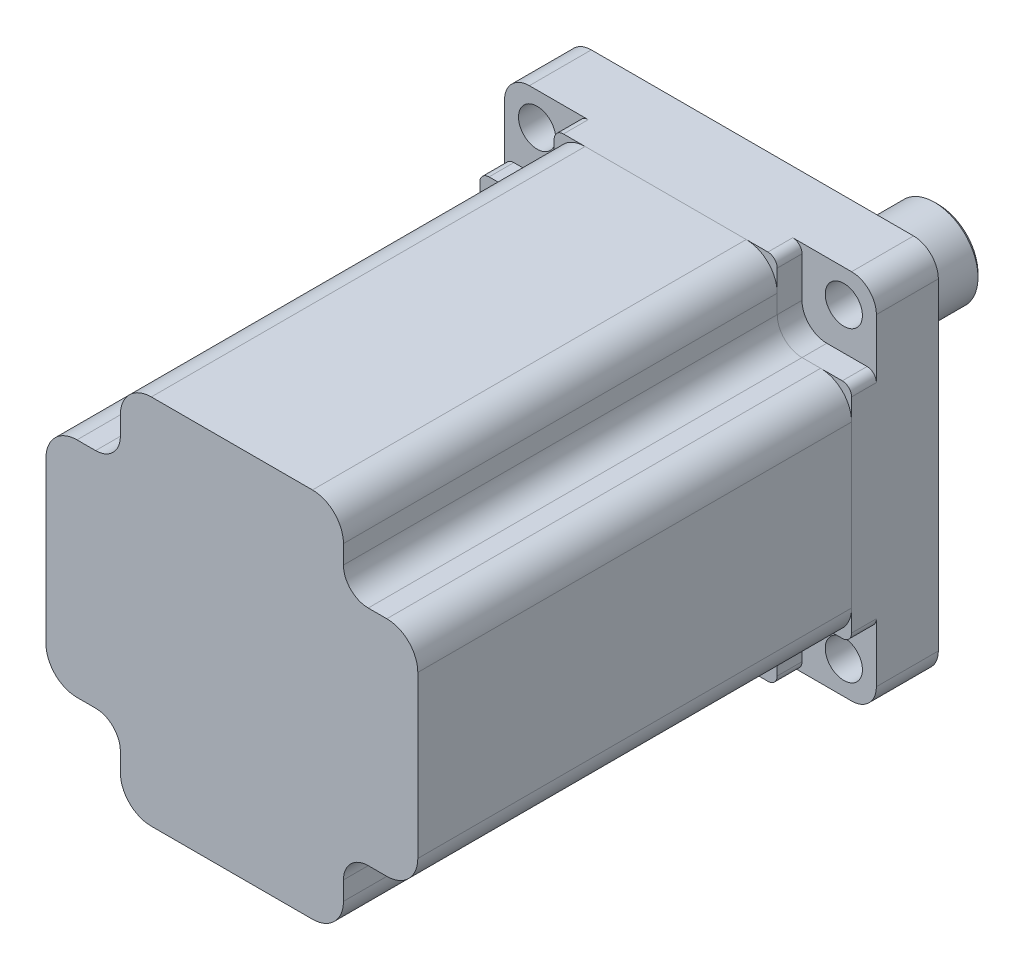
SolidWorks part; units mm, degrees
ref_plane "前视基准面" through (0, 0, 0) normal (0, 0, 1) x (1, 0, 0)
ref_plane "上视基准面" through (0, 0, 0) normal (0, 1, 0) x (1, 0, 0)
ref_plane "右视基准面" through (0, 0, 0) normal (1, 0, 0) x (0, 0, -1)
ref_plane "基准面4" through (0, 0, 0) normal (0, 0, -1) x (-1, 0, 0)
sketch "草图1" plane through (0, 0, 0) normal (0, 0, -1) x (-1, 0, 0)
  line L0 (-30, 30) -> (-30, -30)
  line L1 (-30, -30) -> (30, -30)
  line L2 (30, -30) -> (30, 30)
  line L3 (30, 30) -> (-30, 30)
extrude "凸台-拉伸1" add sketch "草图1" against normal blind 14
sketch "草图2" plane through (30, 0, 0) normal (1, 0, 0) x (0, 0, -1)
  line L0 (-10, 18) -> (-10, 30)
  line L1 (-10, 30) -> (-14, 30)
  line L2 (-14, 30) -> (-14, 18)
  line L3 (-14, 18) -> (-10, 18)
extrude "切除-拉伸1" cut sketch "草图2" against normal blind 12
sketch "草图3" plane through (0, 30, 0) normal (0, 1, 0) x (-1, 0, 0)
  line L0 (18, 14) -> (18, 10)
  line L1 (18, 10) -> (30, 10)
  line L2 (30, 10) -> (30, 14)
  line L3 (30, 14) -> (18, 14)
extrude "切除-拉伸2" cut sketch "草图3" against normal blind 12
sketch "草图4" plane through (-30, 0, 0) normal (-1, 0, 0) x (0, 0, 1)
  line L0 (10, -18) -> (10, -30)
  line L1 (10, -30) -> (14, -30)
  line L2 (14, -30) -> (14, -18)
  line L3 (14, -18) -> (10, -18)
extrude "切除-拉伸3" cut sketch "草图4" against normal blind 12
sketch "草图5" plane through (30, 0, 0) normal (1, 0, 0) x (0, 0, -1)
  line L0 (-14, -30) -> (-10, -30)
  line L1 (-10, -30) -> (-10, -18)
  line L2 (-10, -18) -> (-14, -18)
  line L3 (-14, -18) -> (-14, -30)
extrude "切除-拉伸4" cut sketch "草图5" against normal blind 12
sketch "草图6" plane through (0, 0, 0) normal (0, 1, 0) x (1, 0, 0)
  line L0 (7, 30) -> (0, 30)
  line L1 (0, 30) -> (0, 0)
  line L2 (0, 0) -> (20, 0)
  line L3 (20, 0) -> (20, 3)
  line L4 (20, 3) -> (7, 3)
  line L5 (7, 3) -> (7, 30)
  line L6 (0, 30) -> (0, 0) construction
  dimension "D1" = 20
revolve "旋转1" add sketch "草图6" angle 360 about L6
hole_wizard "Ø6.0 (6) 直径孔1" positions "草图8" profile "草图7" hole size "Ø6.0" standard "ANSI Metric"
sketch "草图8" plane through (0, 0, 10) normal (0, 0, 1) x (1, 0, 0)
  point P0 (-24.7487, -24.7487)
  point P1 (24.7487, -24.7487)
sketch "草图7" plane through (-24.7487, -24.7487, 10) normal (1, 0, 0) x (0, -1, 0)
  line L0 (0, 0) -> (0, 40)
  line L1 (0, 40) -> (3, 40)
  line L2 (3, 40) -> (3, 0)
  line L5 (3, 0) -> (0, 0)
  line L11 (0, -6.35) -> (0, 107.95) construction
  dimension "通孔孔直径" = 6
  dimension "通孔孔深度" = 40
hole_wizard "Ø6.0 (6) 直径孔2" positions "草图10" profile "草图9" hole size "Ø6.0" standard "ANSI Metric"
sketch "草图10" plane through (0, 0, 0) normal (0, 0, -1) x (-1, 0, 0)
  point P0 (24.7487, 24.7487)
  point P1 (-24.7487, 24.7487)
sketch "草图9" plane through (-24.7487, 24.7487, 0) normal (1, 0, 0) x (0, 1, 0)
  line L0 (0, 0) -> (0, 14)
  line L1 (0, 14) -> (3, 14)
  line L2 (3, 14) -> (3, 0)
  line L5 (3, 0) -> (0, 0)
  line L11 (0, -6.35) -> (0, 107.95) construction
  dimension "通孔孔直径" = 6
  dimension "通孔孔深度" = 14
chamfer "倒角1" distance 0.6 angle 45 1 edges at (7, 0, -30)
fillet "圆角1" radius 1.5 8 edges at (-18, 30, 12) (-18, -30, 12) (30, -18, 12) (30, 18, 12) (18, -30, 12) (-30, 18, 12) (-30, -18, 12) (18, 30, 12)
fillet "圆角2" radius 4 8 edges at (-18, -18, 12) (18, -18, 12) (-30, -30, 5) (30, 30, 5) (-18, 18, 12) (-30, 30, 5) (30, -30, 5) (18, 18, 12)
ref_plane "基准面5" through (30, 0, 0) normal (1, 0, 0) x (0, 0, -1)
sketch "草图15" plane through (30, 0, 0) normal (1, 0, 0) x (0, 0, -1)
  line L0 (-89, -30) -> (-14, -30)
  line L2 (-14, -30) -> (-14, 30)
  line L3 (-14, 30) -> (-89, 30)
  line L4 (-89, -30) -> (-89, 30)
  dimension "D2" = 75
extrude "凸台-拉伸2" add sketch "草图15" against normal blind 60 separate body
ref_plane "基准面6" through (0, 0, 14) normal (0, 0, -1) x (-1, 0, 0)
sketch "草图21" plane through (0, 0, 14) normal (0, 0, -1) x (-1, 0, 0)
  line L0 (30, -18) -> (18, -18)
  line L1 (18, -18) -> (18, -30)
  line L2 (18, -30) -> (30, -30)
  line L3 (30, -30) -> (30, -18)
extrude "切除-拉伸5" cut sketch "草图21" against normal through all
ref_plane "基准面7" through (-13.5, 0, 0) normal (-1, 0, 0) x (0, 0, 1)
ref_plane "基准面8" through (0, -30, 0) normal (0, -1, 0) x (-1, 0, 0)
sketch "草图43" plane through (0, 0, 14) normal (0, 0, -1) x (-1, 0, 0)
  line L0 (-18, -30) -> (-18, -18)
  line L1 (-18, -18) -> (-30, -18)
  line L2 (-30, -18) -> (-30, -30)
  line L3 (-30, -30) -> (-18, -30)
extrude "切除-拉伸7" cut sketch "草图43" against normal through all
sketch "草图50" plane through (0, 0, 14) normal (0, 0, -1) x (-1, 0, 0)
  line L0 (-30, 18) -> (-18, 18)
  line L1 (-18, 18) -> (-18, 30)
  line L2 (-18, 30) -> (-30, 30)
  line L3 (-30, 30) -> (-30, 18)
extrude "切除-拉伸8" cut sketch "草图50" against normal through all
sketch "草图57" plane through (0, 0, 14) normal (0, 0, -1) x (-1, 0, 0)
  line L0 (18, 30) -> (18, 18)
  line L1 (18, 18) -> (30, 18)
  line L2 (30, 18) -> (30, 30)
  line L3 (30, 30) -> (18, 30)
extrude "切除-拉伸9" cut sketch "草图57" against normal through all
ref_plane "基准面9" through (0, -39, 0) normal (0, -1, 0) x (-1, 0, 0)
ref_plane "基准面10" through (0, 0, 98.5) normal (0, 0, 1) x (1, 0, 0)
ref_plane "基准面11" through (0, 30, 0) normal (0, 1, 0) x (1, 0, 0)
ref_plane "基准面12" through (-30, 0, 0) normal (-1, 0, 0) x (0, 0, 1)
fillet "圆角5" radius 4 4 edges at (18, 18, 51.5) (18, -18, 51.5) (-18, 18, 51.5) (-18, -18, 51.5)
fillet "圆角6" radius 5 8 edges at (18, -30, 51.5) (30, -18, 51.5) (30, 18, 51.5) (18, 30, 51.5) (-18, 30, 51.5) (-30, 18, 51.5) (-30, -18, 51.5) (-18, -30, 51.5)
sketch "草图58" plane through (30, 0, 0) normal (1, 0, 0) x (0, 0, -1)
  line L0 (-89, 30) -> (-89, -30)
  line L1 (-89, -30) -> (-84, -30)
  line L2 (-14, -30) -> (-89, -30) construction
  line L3 (-84, -30) -> (-84, 30)
  line L4 (-89, 30) -> (-14, 30) construction
  line L5 (-84, 30) -> (-89, 30)
  dimension "D1" = 5
extrude "切除-拉伸10" cut sketch "草图58" against normal blind 86
